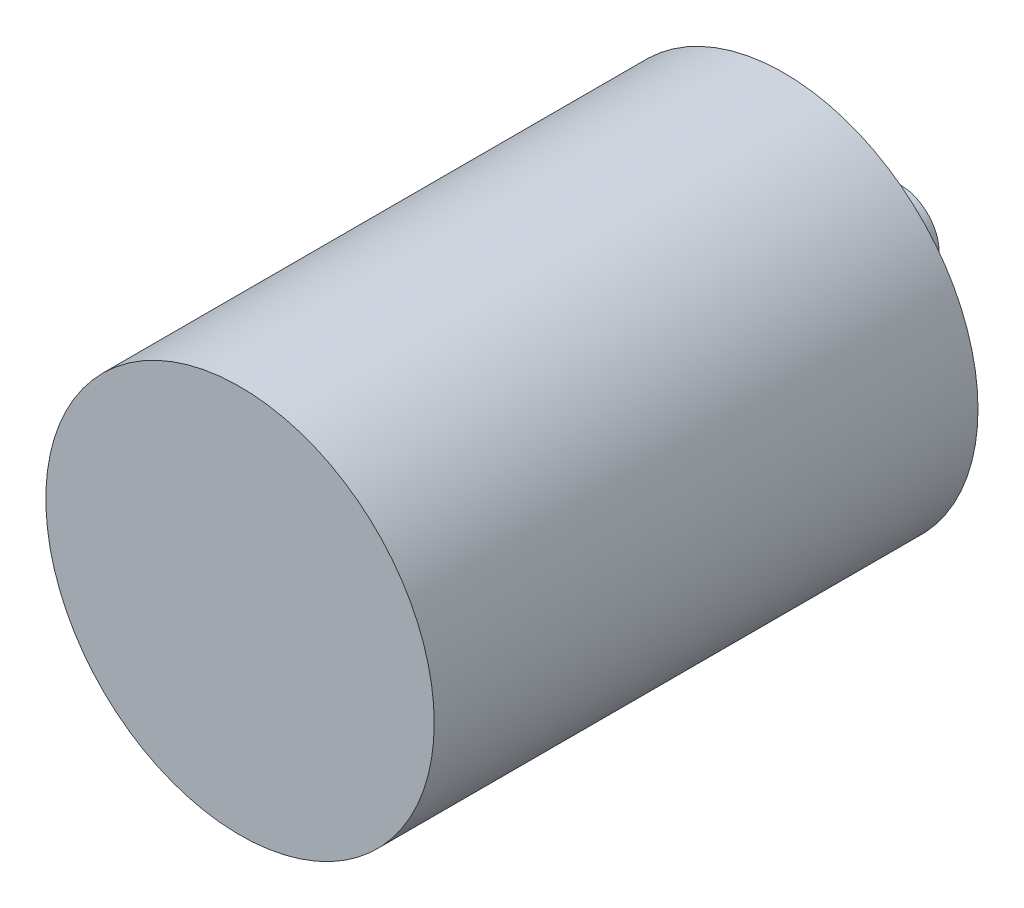
SolidWorks part; units mm, degrees
ref_plane "Front Plane" through (0, 0, 0) normal (0, 0, 1) x (1, 0, 0)
ref_plane "Top Plane" through (0, 0, 0) normal (0, 1, 0) x (1, 0, 0)
ref_plane "Right Plane" through (0, 0, 0) normal (1, 0, 0) x (0, 0, -1)
sketch "Sketch1" plane through (0, 0, 0) normal (0, 0, 1) x (1, 0, 0)
  circle A0 centre (0, 0) radius 10
  dimension "D1" = 20
extrude "Boss-Extrude1" add sketch "Sketch1" along normal blind 28
sketch "Sketch2" plane through (0, 0, 0) normal (0, 0, -1) x (-1, 0, 0)
  circle A0 centre (0, 0) radius 2
  dimension "D1" = 4
extrude "Boss-Extrude2" add sketch "Sketch2" along normal blind 6 contours A0
equation "\"motor_diameter\"=20"
equation "\"D1@Sketch1\"=\"motor_diameter\""
equation "\"motor_length\"= 28"
equation "\"D1@Boss-Extrude1\"=\"motor_length\""
equation "\"motor_shaft_d\"=4"
equation "\"D1@Sketch2\"=\"motor_shaft_d\""
equation "\"shaft_length\"=6"
equation "\"D1@Boss-Extrude2\"=\"shaft_length\""
